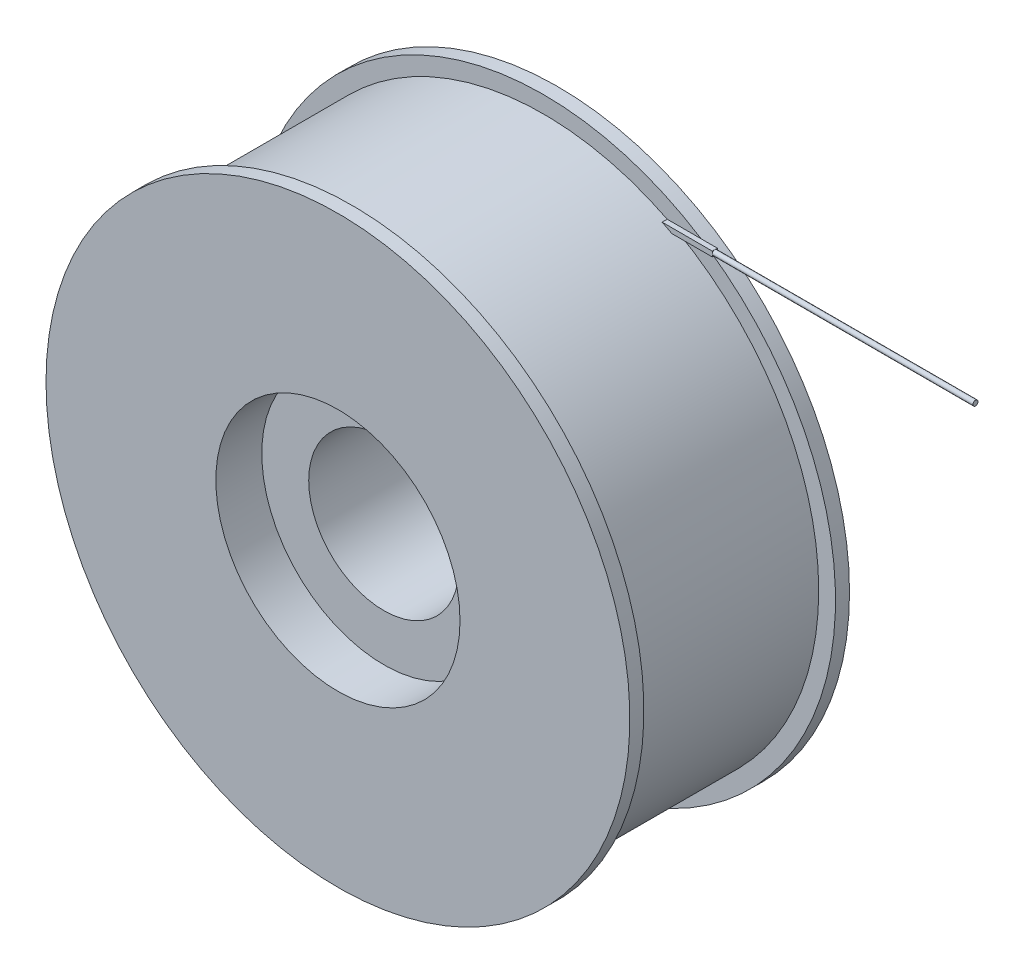
SolidWorks part; units mm, degrees
ref_plane "Front Plane" through (0, 0, 0) normal (0, 0, 1) x (1, 0, 0)
ref_plane "Top Plane" through (0, 0, 0) normal (0, 1, 0) x (1, 0, 0)
ref_plane "Right Plane" through (0, 0, 0) normal (1, 0, 0) x (0, 0, -1)
sketch "Sketch1" plane through (0, 0, 0) normal (0, 0, 1) x (1, 0, 0)
  circle A0 centre (0, 0) radius 100.8
  circle A1 centre (0, 0) radius 25.95
  dimension "D1" = 201.6
  dimension "D2" = 51.9
extrude "Boss-Extrude1" add sketch "Sketch1" along normal blind 4.84
sketch "Sketch2" plane through (0, 0, 4.84) normal (0, 0, 1) x (1, 0, 0)
  circle A0 centre (0, 0) radius 25.95
  circle A1 centre (0, 0) radius 45.11
  circle A2 centre (0, 0) radius 25.95 construction
  dimension "D1" = 90.22
extrude "Boss-Extrude2" add sketch "Sketch2" along normal blind 66.17
sketch "Sketch3" plane through (0, 0, 71.01) normal (0, 0, 1) x (1, 0, 0)
  circle A0 centre (0, 0) radius 25.95 construction
  circle A1 centre (0, 0) radius 25.95
  circle A2 centre (0, 0) radius 100.8
  circle A3 centre (0, 0) radius 100.8 construction
extrude "Boss-Extrude3" add sketch "Sketch3" along normal blind 4.84
sketch "Sketch4" plane through (0, 0, 75.85) normal (0, 0, 1) x (1, 0, 0)
  circle A0 centre (0, 0) radius 42.16
  dimension "D1" = 84.32
extrude "Cut-Extrude1" cut sketch "Sketch4" against normal blind 15.86
sketch "Sketch5" plane through (0, 0, 71.01) normal (0, 0, -1) x (-1, 0, 0)
  circle A1 centre (0, 0) radius 100.8
  circle A2 centre (0, 0) radius 100.8
  circle A3 centre (0, 0) radius 45.11
  circle A4 centre (0, 0) radius 45.11
  circle A9 centre (0, 0) radius 95
  circle M4 centre (0, 0) radius 45.11
  dimension "D3" = 190
  dimension "D1" = 0
  dimension "D2" = 0
extrude "Boss-Extrude4" add sketch "Sketch5" along normal up to surface (66.17 mm away) contours A9 M4 up to face at (100.8, 0, 4.84)
sketch "Sketch6" plane through (0, 0, 4.84) normal (0, 0, 1) x (1, 0, 0)
  line L0 (0, -84.87) -> (0, -83.995)
  line L3 (0, -84.87) -> (150, -84.87)
  line L4 (0, -84.87) -> (0, -83.12)
  line L5 (0, -83.12) -> (150, -83.12)
  line L6 (150, -84.87) -> (150, -83.12)
  dimension "D1" = 0.875
  dimension "D2" = 1.75
  dimension "D3" = 150
extrude "Boss-Extrude5" add sketch "Sketch6" along normal blind 1.75 contours L4 L5 L6 L3
sketch "Sketch7" plane through (150, 0, 0) normal (1, 0, 0) x (0, 0, -1)
  line L0 (-6.59, -83.12) -> (-4.84, -84.87) construction
  line L2 (-6.59, -83.12) -> (-4.84, -83.12)
  line L3 (-6.59, -83.12) -> (-6.59, -84.87)
  line L4 (-6.59, -84.87) -> (-4.84, -84.87)
  line L5 (-4.84, -83.12) -> (-4.84, -84.87)
  circle A0 centre (-5.715, -83.995) radius 0.875
  line M1 (-4.84, -84.87) -> (-4.84, -83.12)
  line M2 (-4.84, -83.12) -> (-6.59, -83.12)
  line M3 (-6.59, -83.12) -> (-6.59, -84.87)
  line M4 (-6.59, -84.87) -> (-4.84, -84.87)
extrude "Cut-Extrude5" cut sketch "Sketch7" against normal blind 90 contours L0 A0 M3 | L2 L0 A0 | A0 L5 M2 | A0 L0 M1 | L0 A0 L4 | A0 L3 M4
mirror "Mirror5" about plane through (0, 0, 0) normal (0, 1, 0) of "Boss-Extrude4", "Boss-Extrude5", "Cut-Extrude5"
sketch "Sketch11" plane through (0, -84.87, 0) normal (0, -1, 0) x (1, 0, 0)
  line L0 (42.6859, 6.59) -> (60, 6.59) construction
  line L1 (48.8267, 6.59) -> (150, 6.59)
  line L2 (48.8267, 6.59) -> (48.8267, 4.84)
  line L3 (48.8267, 4.84) -> (150, 4.84)
  line L4 (150, 6.59) -> (150, 4.84)
extrude "Cut-Extrude6" cut sketch "Sketch11" against normal up to surface (1.75 mm away) up to face at (54.8375, -83.12, 5.5692)
